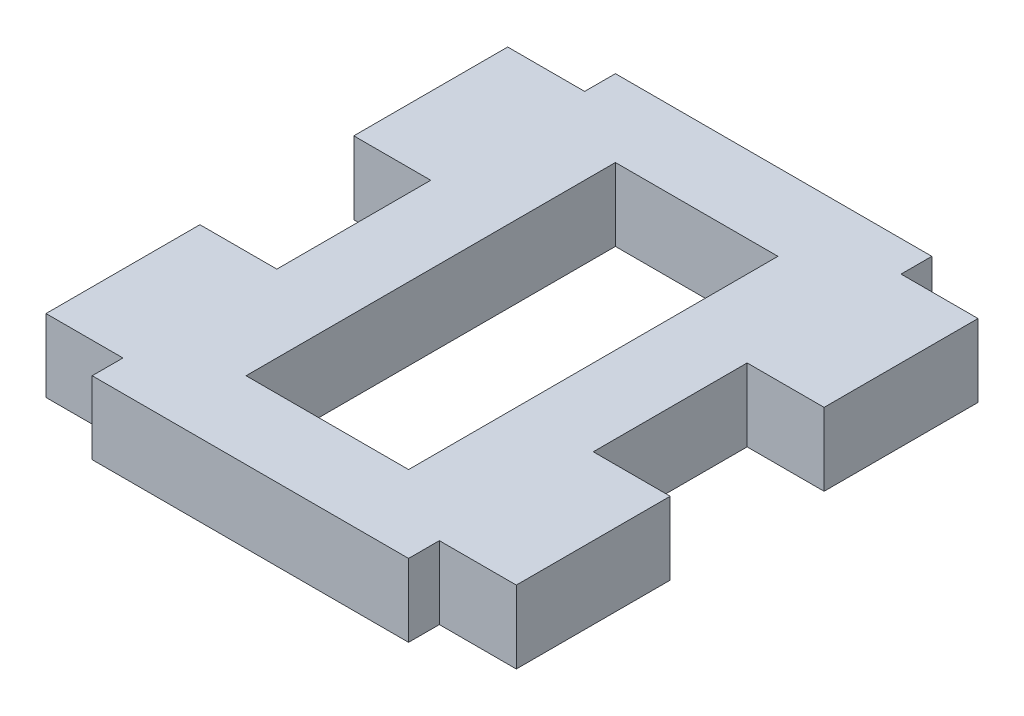
SolidWorks part; units mm, degrees
ref_plane "Front Plane" through (0, 0, 0) normal (0, 0, 1) x (1, 0, 0)
ref_plane "Top Plane" through (0, 0, 0) normal (0, 1, 0) x (1, 0, 0)
ref_plane "Right Plane" through (0, 0, 0) normal (1, 0, 0) x (0, 0, -1)
sketch "Sketch1" plane through (0, 0, 0) normal (0, 1, 0) x (1, 0, 0)
  line L1 (-13.0556, -21.59) -> (13.0556, -21.59)
  line L2 (-13.0556, -21.59) -> (-13.0556, 21.59)
  line L3 (-13.0556, 21.59) -> (13.0556, 21.59)
  line L4 (13.0556, -21.59) -> (13.0556, 21.59)
  line L5 (-13.0556, -21.59) -> (13.0556, 21.59) construction
  line L6 (-13.0556, 21.59) -> (13.0556, -21.59) construction
  point P0 (0, 0)
  dimension "D1" = 26.1112
  dimension "D2" = 43.18
extrude "Boss-Extrude1" add sketch "Sketch1" along normal blind 6
sketch "Sketch2" plane through (0, 0, 0) normal (0, -1, 0) x (1, 0, 0)
  line L0 (-13.0556, 19.05) -> (-19.4056, 19.05)
  line L1 (-13.0556, -21.59) -> (-13.0556, 21.59) construction
  line L2 (-19.4056, 19.05) -> (-19.4056, 6.35)
  line L3 (-19.4056, 6.35) -> (-13.0556, 6.35)
  line L4 (-13.0556, 6.35) -> (-13.0556, 19.05)
  line L5 (-13.0556, 0) -> (13.0556, 0) construction
  line L6 (13.0556, 21.59) -> (13.0556, -21.59) construction
  line L7 (0, -21.59) -> (0, 21.59) construction
  line L8 (-13.0556, 21.59) -> (13.0556, 21.59) construction
  line L9 (13.0556, 6.35) -> (13.0556, 19.05)
  line L10 (19.4056, 6.35) -> (13.0556, 6.35)
  line L11 (19.4056, 19.05) -> (19.4056, 6.35)
  line L12 (13.0556, 19.05) -> (19.4056, 19.05)
  line L13 (13.0556, -19.05) -> (19.4056, -19.05)
  line L14 (19.4056, -19.05) -> (19.4056, -6.35)
  line L15 (19.4056, -6.35) -> (13.0556, -6.35)
  line L16 (13.0556, -6.35) -> (13.0556, -19.05)
  line L17 (-13.0556, -6.35) -> (-13.0556, -19.05)
  line L18 (-19.4056, -6.35) -> (-13.0556, -6.35)
  line L19 (-19.4056, -19.05) -> (-19.4056, -6.35)
  line L20 (-13.0556, -19.05) -> (-19.4056, -19.05)
  point P12 (0, 0)
  point P18 (0, 0)
  dimension "D1" = 12.7
  dimension "D2" = 6.35
  dimension "D3" = 6.35
extrude "Boss-Extrude2" add sketch "Sketch2" against normal up to surface (6 mm away) up to face at (0, 6, 0)
sketch "Sketch3" plane through (0, 0, 0) normal (0, -1, 0) x (1, 0, 0)
  line L0 (-13.0556, 21.59) -> (13.0556, 21.59) construction
  line L1 (-6.7056, -15.24) -> (6.7056, -15.24)
  line L2 (-6.7056, -15.24) -> (-6.7056, 15.24)
  line L3 (-6.7056, 15.24) -> (6.7056, 15.24)
  line L4 (6.7056, -15.24) -> (6.7056, 15.24)
  line L5 (-6.7056, -15.24) -> (6.7056, 15.24) construction
  line L6 (-6.7056, 15.24) -> (6.7056, -15.24) construction
  line L7 (13.0556, 6.35) -> (13.0556, -6.35) construction
  point P0 (0, 0)
  dimension "D1" = 6.35
  dimension "D2" = 6.35
extrude "Cut-Extrude1" cut sketch "Sketch3" against normal through all
